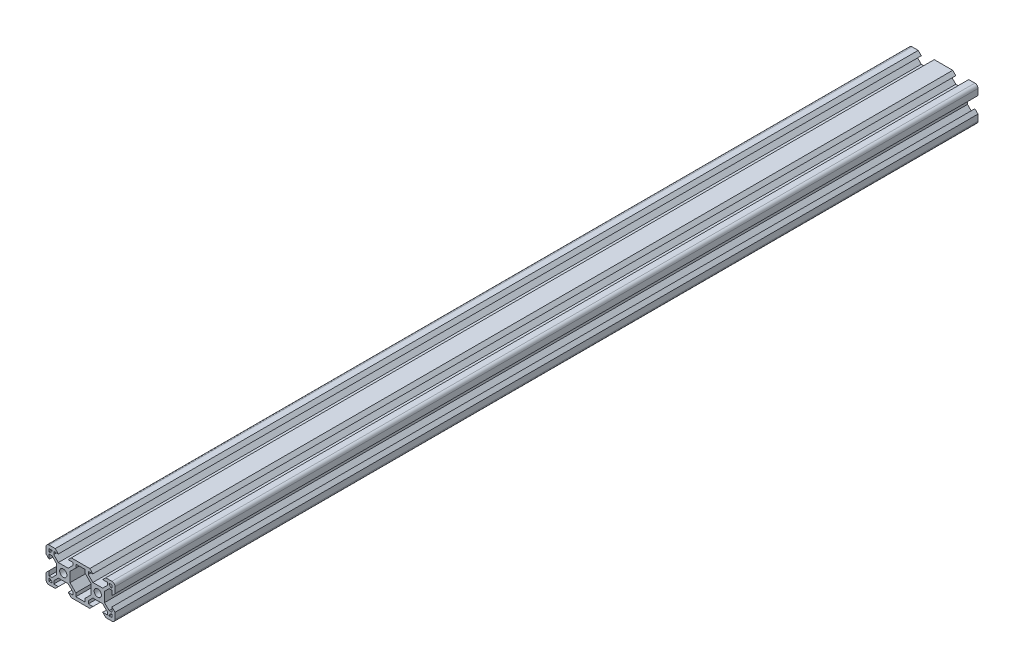
SolidWorks part; units mm, degrees
material "5052-H38, Barre (SS)"
ref_plane "Plan de face" through (0, 0, 0) normal (0, 0, 1) x (1, 0, 0)
ref_plane "Plan de dessus" through (0, 0, 0) normal (0, 1, 0) x (1, 0, 0)
ref_plane "Plan de droite" through (0, 0, 0) normal (1, 0, 0) x (0, 0, -1)
sketch "Esquisse1" plane through (0, 0, 0) normal (0, 0, 1) x (1, 0, 0)
  line L0 (0, 0) -> (0, 10) construction
  line L1 (0, 0) -> (-20, 0) construction
  line L2 (-10, 0) -> (-20, 10) construction
  line L3 (-10, 3.9007) -> (-12.84, 3.9007)
  line L4 (-12.84, 3.9007) -> (-15.4993, 6.56)
  line L5 (-15.4993, 6.56) -> (-15.4993, 8.2)
  line L6 (-15.4993, 8.2) -> (-12.84, 8.2)
  line L7 (-12.84, 8.2) -> (-14.64, 10)
  line L8 (-14.64, 10) -> (-18.2, 10)
  line L9 (-10, 0) -> (-10, 10) construction
  line L10 (-20, 4.64) -> (-20, 8.2)
  line L11 (-18.2, 2.84) -> (-20, 4.64)
  line L12 (-18.2, 5.4993) -> (-18.2, 2.84)
  line L13 (-16.56, 5.4993) -> (-18.2, 5.4993)
  line L14 (-13.9007, 2.84) -> (-16.56, 5.4993)
  line L15 (-13.9007, 0) -> (-13.9007, 2.84)
  line L16 (-10, -3.9007) -> (-12.84, -3.9007)
  line L17 (-12.84, -3.9007) -> (-15.4993, -6.56)
  line L18 (-15.4993, -6.56) -> (-15.4993, -8.2)
  line L19 (-15.4993, -8.2) -> (-12.84, -8.2)
  line L20 (-12.84, -8.2) -> (-14.64, -10)
  line L21 (-14.64, -10) -> (-18.2, -10)
  line L22 (-20, -4.64) -> (-20, -8.2)
  line L23 (-18.2, -2.84) -> (-20, -4.64)
  line L24 (-18.2, -5.4993) -> (-18.2, -2.84)
  line L25 (-16.56, -5.4993) -> (-18.2, -5.4993)
  line L26 (-13.9007, -2.84) -> (-16.56, -5.4993)
  line L27 (-13.9007, 0) -> (-13.9007, -2.84)
  line L28 (-10, 0) -> (0, 10) construction
  line L29 (-10, 3.9007) -> (-7.16, 3.9007)
  line L30 (-7.16, 3.9007) -> (-4.5007, 6.56)
  line L31 (-4.5007, 6.56) -> (-4.5007, 8.2)
  line L32 (-4.5007, 8.2) -> (-7.16, 8.2)
  line L33 (-7.16, 8.2) -> (-5.36, 10)
  line L34 (-7.16, -8.2) -> (-5.36, -10)
  line L35 (-4.5007, -8.2) -> (-7.16, -8.2)
  line L36 (-4.5007, -6.56) -> (-4.5007, -8.2)
  line L37 (-7.16, -3.9007) -> (-4.5007, -6.56)
  line L38 (-10, -3.9007) -> (-7.16, -3.9007)
  line L39 (-5.36, 10) -> (5.36, 10)
  line L40 (-5.36, -10) -> (5.36, -10)
  line L41 (-2.7, 8.2) -> (-2.7, 6.2393)
  line L42 (-2.7, 6.2393) -> (-6.0993, 2.84)
  line L43 (-2.7, 8.2) -> (2.7, 8.2)
  line L44 (-6.0993, 2.84) -> (-6.0993, -2.84)
  line L45 (-7.16, 3.9007) -> (-6.0993, 2.84) construction
  line L46 (-2.7, -8.2) -> (2.7, -8.2)
  line L47 (-2.7, -8.2) -> (-2.7, -6.2393)
  line L48 (-2.7, -6.2393) -> (-6.0993, -2.84)
  line L49 (-18.2, 8.2) -> (-18.2, 6.5693)
  line L50 (-18.2, 6.5693) -> (-17.63, 6.5693)
  line L51 (-17.63, 6.5693) -> (-16.5693, 7.63)
  line L52 (-16.5693, 7.63) -> (-16.5693, 8.2)
  line L53 (-16.5693, 8.2) -> (-18.2, 8.2)
  line L54 (-18.2, -6.5693) -> (-17.63, -6.5693)
  line L55 (-18.2, -8.2) -> (-18.2, -6.5693)
  line L56 (-16.5693, -8.2) -> (-18.2, -8.2)
  line L57 (-16.5693, -7.63) -> (-16.5693, -8.2)
  line L58 (-17.63, -6.5693) -> (-16.5693, -7.63)
  line L59 (18.2, 6.5693) -> (17.63, 6.5693)
  line L60 (18.2, 8.2) -> (18.2, 6.5693)
  line L61 (16.5693, 8.2) -> (18.2, 8.2)
  line L62 (16.5693, 7.63) -> (16.5693, 8.2)
  line L63 (17.63, 6.5693) -> (16.5693, 7.63)
  line L64 (18.2, -6.5693) -> (17.63, -6.5693)
  line L65 (18.2, -8.2) -> (18.2, -6.5693)
  line L66 (16.5693, -8.2) -> (18.2, -8.2)
  line L67 (16.5693, -7.63) -> (16.5693, -8.2)
  line L68 (17.63, -6.5693) -> (16.5693, -7.63)
  line L69 (2.7, 8.2) -> (2.7, 6.2393)
  line L70 (2.7, 6.2393) -> (6.0993, 2.84)
  line L71 (6.0993, 2.84) -> (6.0993, -2.84)
  line L72 (2.7, -6.2393) -> (6.0993, -2.84)
  line L73 (2.7, -8.2) -> (2.7, -6.2393)
  line L74 (7.16, -8.2) -> (5.36, -10)
  line L75 (4.5007, -8.2) -> (7.16, -8.2)
  line L76 (4.5007, -6.56) -> (4.5007, -8.2)
  line L77 (7.16, -3.9007) -> (4.5007, -6.56)
  line L78 (10, -3.9007) -> (7.16, -3.9007)
  line L79 (10, -3.9007) -> (12.84, -3.9007)
  line L80 (12.84, -3.9007) -> (15.4993, -6.56)
  line L81 (15.4993, -6.56) -> (15.4993, -8.2)
  line L82 (15.4993, -8.2) -> (12.84, -8.2)
  line L83 (12.84, -8.2) -> (14.64, -10)
  line L84 (14.64, -10) -> (18.2, -10)
  line L85 (20, -4.64) -> (20, -8.2)
  line L86 (18.2, -2.84) -> (20, -4.64)
  line L87 (18.2, -5.4993) -> (18.2, -2.84)
  line L88 (16.56, -5.4993) -> (18.2, -5.4993)
  line L89 (13.9007, -2.84) -> (16.56, -5.4993)
  line L90 (13.9007, 0) -> (13.9007, -2.84)
  line L91 (13.9007, 0) -> (13.9007, 2.84)
  line L92 (13.9007, 2.84) -> (16.56, 5.4993)
  line L93 (16.56, 5.4993) -> (18.2, 5.4993)
  line L94 (18.2, 5.4993) -> (18.2, 2.84)
  line L95 (18.2, 2.84) -> (20, 4.64)
  line L96 (20, 4.64) -> (20, 8.2)
  line L97 (14.64, 10) -> (18.2, 10)
  line L98 (12.84, 8.2) -> (14.64, 10)
  line L99 (15.4993, 8.2) -> (12.84, 8.2)
  line L100 (15.4993, 6.56) -> (15.4993, 8.2)
  line L101 (12.84, 3.9007) -> (15.4993, 6.56)
  line L102 (10, 3.9007) -> (12.84, 3.9007)
  line L103 (10, 3.9007) -> (7.16, 3.9007)
  line L104 (7.16, 3.9007) -> (4.5007, 6.56)
  line L105 (4.5007, 6.56) -> (4.5007, 8.2)
  line L106 (4.5007, 8.2) -> (7.16, 8.2)
  line L107 (7.16, 8.2) -> (5.36, 10)
  circle A0 centre (-10, 0) radius 2.1
  arc A1 (-18.2, 10) -> (-20, 8.2) centre (-18.2, 8.2) ccw
  arc A2 (-20, -8.2) -> (-18.2, -10) centre (-18.2, -8.2) ccw
  circle A3 centre (10, 0) radius 2.1
  arc A4 (20, -8.2) -> (18.2, -10) centre (18.2, -8.2) cw
  arc A5 (18.2, 10) -> (20, 8.2) centre (18.2, 8.2) cw
  point P57 (-6.0993, 0)
  point P61 (-17.0997, 7.0997)
  point P80 (0, 8.2)
  point P85 (0, -8.2)
  point P86 (0, -10)
  dimension "D3" = 4.2
  dimension "D2" = 20
  dimension "D4" = 5.68
  dimension "D5" = 1.5
  dimension "D6" = 1.8
  dimension "D7" = 1.64
  dimension "D11" = 5.4
  dimension "D12" = 1.07
  dimension "D8" = 2
  dimension "D9" = 2
  dimension "D10" = 2
extrude "Boss.-Extru.1" add sketch "Esquisse1" along normal mid plane 500
